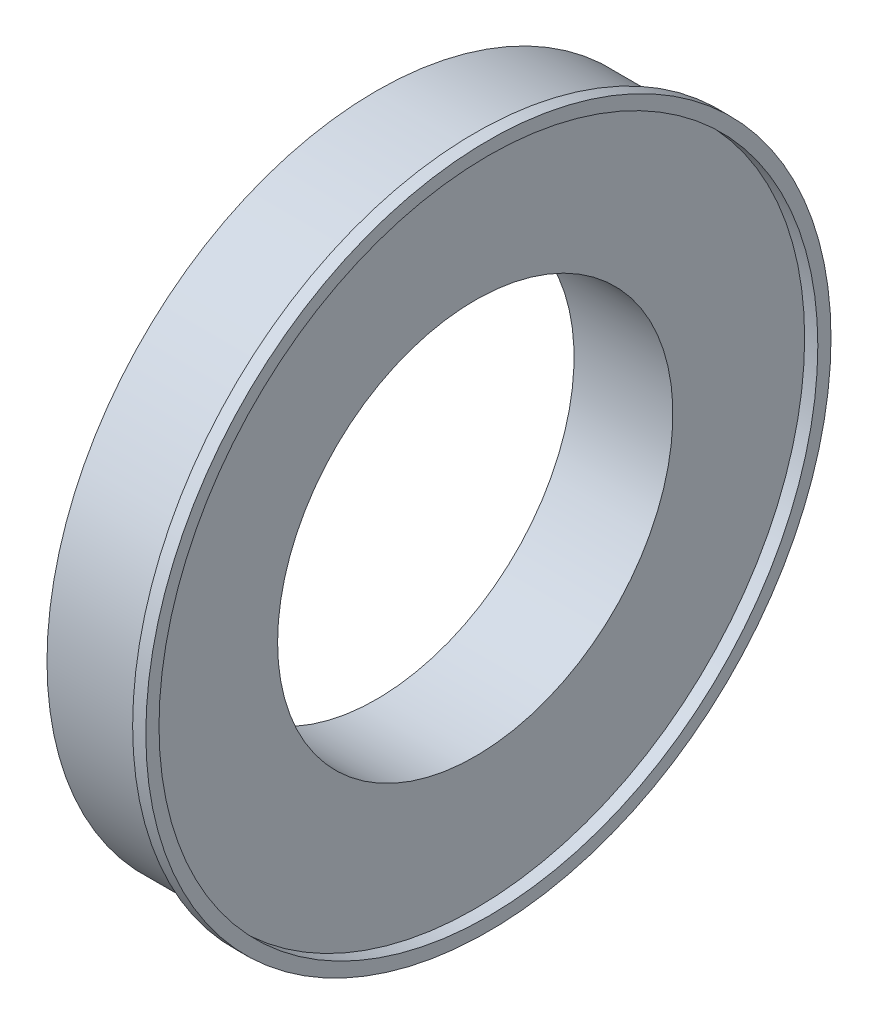
SolidWorks part; units mm, degrees
ref_plane "Front Plane" through (0, 0, 0) normal (0, 0, 1) x (1, 0, 0)
ref_plane "Top Plane" through (0, 0, 0) normal (0, 1, 0) x (1, 0, 0)
ref_plane "Right Plane" through (0, 0, 0) normal (1, 0, 0) x (0, 0, -1)
sketch "Sketch1" plane through (0, 0, 0) normal (1, 0, 0) x (0, 0, -1)
  circle A0 centre (0, 0) radius 38.1
  circle A1 centre (0, 0) radius 63.5
  dimension "D1" = 127
  dimension "D2" = 76.2
extrude "Boss-Extrude1" add sketch "Sketch1" along normal blind 19.05
sketch "Sketch2" plane through (19.05, 0, 0) normal (1, 0, 0) x (0, 0, -1)
  circle A1 centre (0, 0) radius 63.5 construction
  circle A2 centre (0, 0) radius 66.04
  circle A3 centre (0, 0) radius 66.04
  circle A4 centre (0, 0) radius 63.5
  dimension "D1" = 2.54
extrude "Boss-Extrude2" add sketch "Sketch2" along normal blind 2.54 separate body
